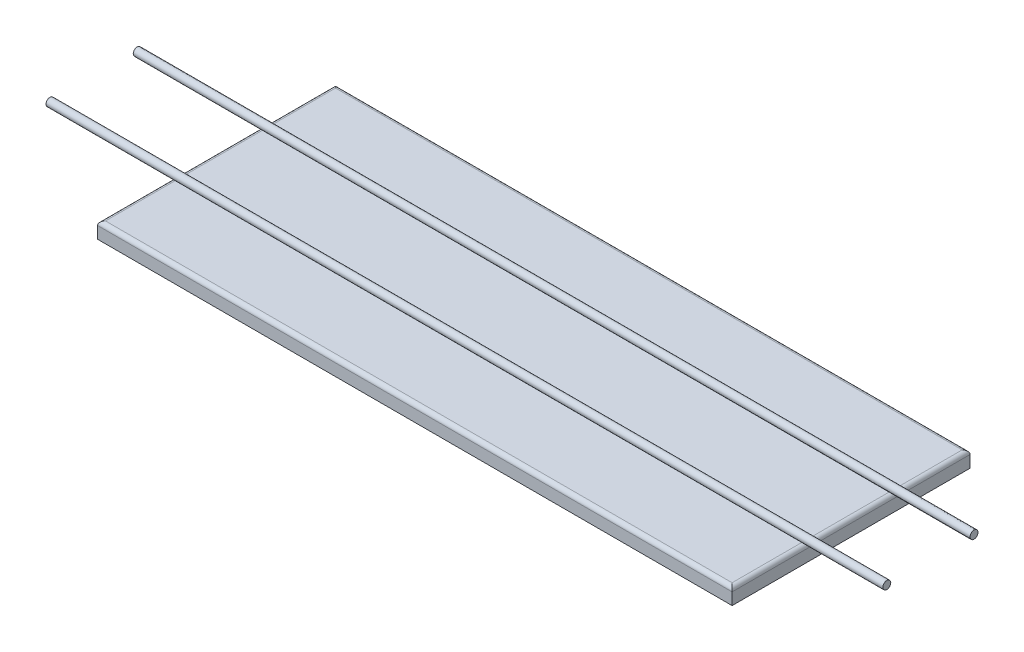
SolidWorks part; units mm, degrees
ref_plane "Alzado" through (0, 0, 0) normal (0, 0, 1) x (1, 0, 0)
ref_plane "Planta" through (0, 0, 0) normal (0, 1, 0) x (1, 0, 0)
ref_plane "Vista lateral" through (0, 0, 0) normal (1, 0, 0) x (0, 0, -1)
sketch "Croquis1" plane through (0, 0, 0) normal (0, 1, 0) x (1, 0, 0)
  line L1 (400, -150) -> (-400, -150)
  line L2 (400, -150) -> (400, 150)
  line L3 (400, 150) -> (-400, 150)
  line L4 (-400, -150) -> (-400, 150)
  line L5 (400, -150) -> (-400, 150) construction
  line L6 (400, 150) -> (-400, -150) construction
  point P0 (0, 0)
  dimension "D1" = 800
  dimension "D2" = 300
extrude "Extruir1" add sketch "Croquis1" along normal blind 20
fillet "Redondeo1" radius 5 4 edges at (0, 20, -150) (400, 20, 0) (0, 20, 150) (-400, 20, 0)
sketch "Croquis2" plane through (0, 0, 0) normal (1, 0, 0) x (0, 0, -1)
  line L0 (-145, 20) -> (145, 20) construction
  line L1 (-145, 20) -> (145, 20) construction
  line L2 (0, 20) -> (0, 88.795) construction
  circle A0 centre (-55, 25) radius 5
  circle A1 centre (55, 25) radius 5
  dimension "D1" = 10
  dimension "D2" = 55
extrude "Extruir2" add sketch "Croquis2" along normal blind 500 and the other way blind 555 separate body
